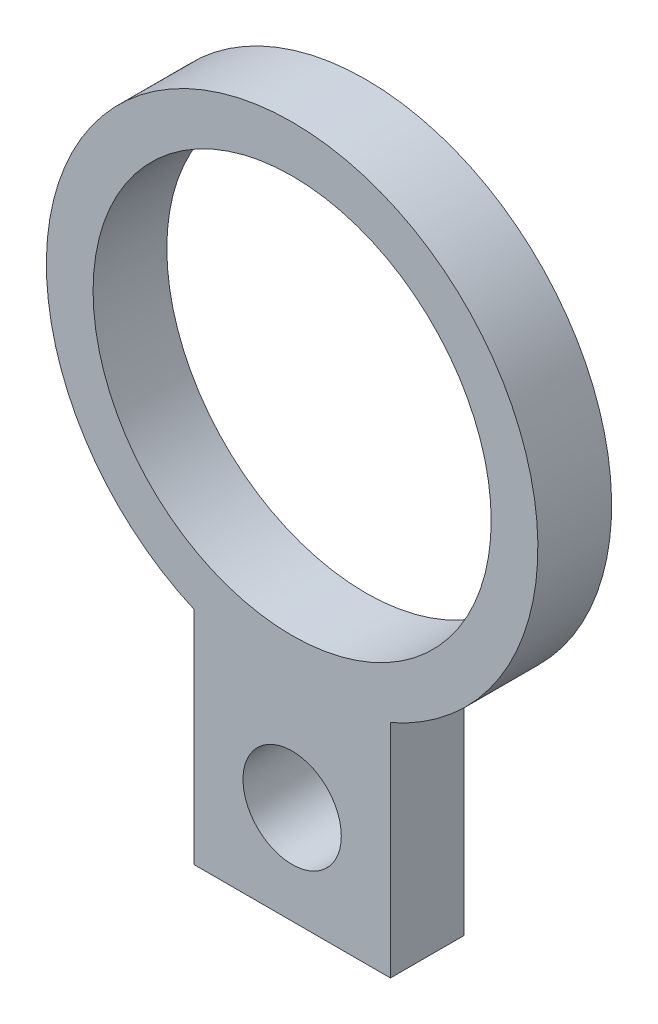
SolidWorks part; units mm, degrees
ref_plane "前视基准面" through (0, 0, 0) normal (0, 0, 1) x (1, 0, 0)
ref_plane "上视基准面" through (0, 0, 0) normal (0, 1, 0) x (1, 0, 0)
ref_plane "右视基准面" through (0, 0, 0) normal (1, 0, 0) x (0, 0, -1)
sketch "草图1" plane through (0, 0, 0) normal (0, 0, 1) x (1, 0, 0)
  line L0 (-2, -9.0826) -> (2, -9.0826)
  line L2 (2, -9.0826) -> (2, -4.5826)
  line L4 (-2, -4.5826) -> (-2, -9.0826)
  line L5 (-2, -6.0826) -> (2, -6.0826) construction
  line L6 (-2, -4.5826) -> (2, -4.5826) construction
  arc A0 (2, -4.5826) -> (-2, -4.5826) centre (0, 0) ccw
  circle A1 centre (0, -7.0826) radius 1
  circle A2 centre (0, 0) radius 4.05
  point P6 (0, -9.0826)
  dimension "D1" = 5
  dimension "D4" = 2
  dimension "D6" = 8.1
  dimension "D2" = 4
  dimension "D3" = 4.5
  dimension "D5" = 1.5
extrude "凸台-拉伸1" add sketch "草图1" along normal blind 1.5
